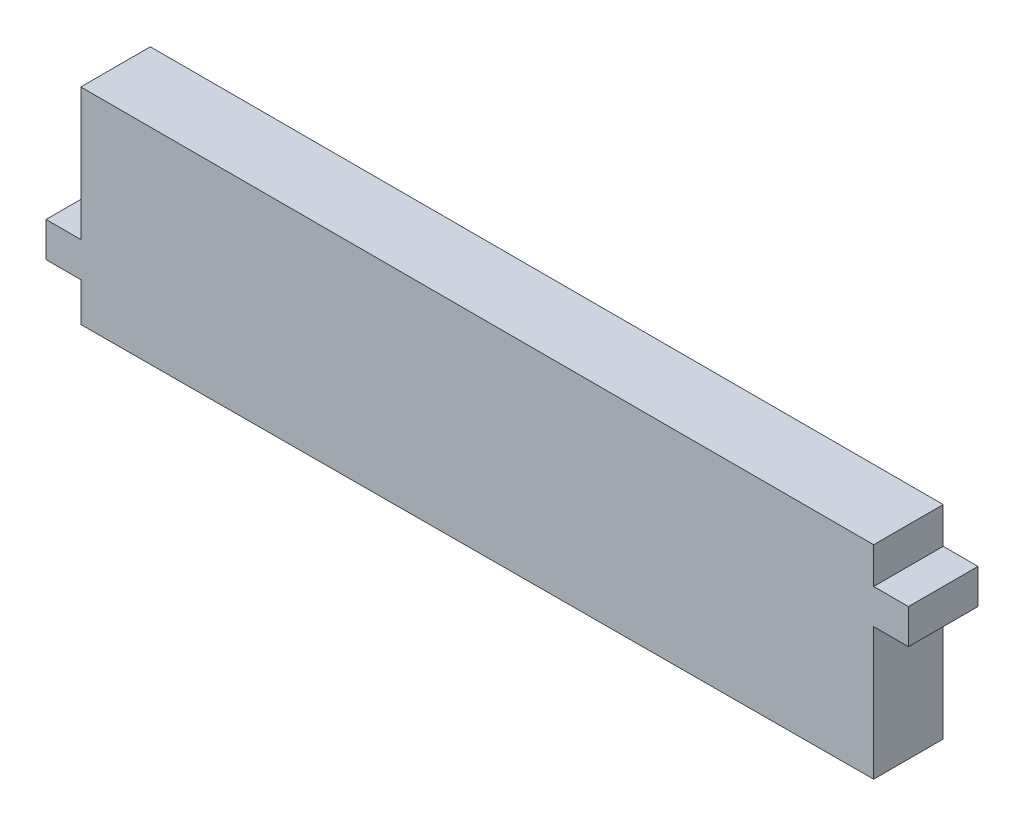
SolidWorks part; units mm, degrees
material "Balsa"
ref_plane "Front Plane" through (0, 0, 0) normal (0, 0, 1) x (1, 0, 0)
ref_plane "Top Plane" through (0, 0, 0) normal (0, 1, 0) x (1, 0, 0)
ref_plane "Right Plane" through (0, 0, 0) normal (1, 0, 0) x (0, 0, -1)
sketch "Sketch1" plane through (0, 0, 0) normal (0, 0, 1) x (1, 0, 0)
  line L0 (15.8059, -23.2483) -> (12.6309, -23.2483)
  line L1 (12.6309, -23.2483) -> (12.6309, -26.4233)
  line L2 (12.6309, -26.4233) -> (15.8059, -26.4233)
  line L3 (88.1959, -14.4853) -> (91.3709, -14.4853)
  line L4 (91.3709, -14.4853) -> (91.3709, -17.6603)
  line L5 (91.3709, -17.6603) -> (88.1959, -17.6603)
  line L6 (88.1959, -32.4488) -> (88.1959, -5.9912) construction
  line L7 (88.1959, -17.6603) -> (88.1959, -23.2483)
  line L8 (88.1959, -14.4853) -> (88.1959, -11.1833)
  line L9 (88.1959, -11.1833) -> (15.8059, -11.1833)
  line L10 (15.8059, -11.1833) -> (15.8059, -23.2483)
  line L11 (88.1959, -23.2483) -> (88.1959, -29.7253)
  line L12 (88.1959, -29.7253) -> (15.8059, -29.9673)
  line L13 (15.8059, -29.9673) -> (15.8059, -26.4233)
  point P19 (88.1959, -20.4543)
  point P21 (88.1959, -11.1833)
  point P22 (88.1959, -29.7253)
  dimension "D1" = 9.271
  dimension "D2" = 9.271
extrude "Boss-Extrude1" add sketch "Sketch1" along normal up to surface (6.35 mm away)
